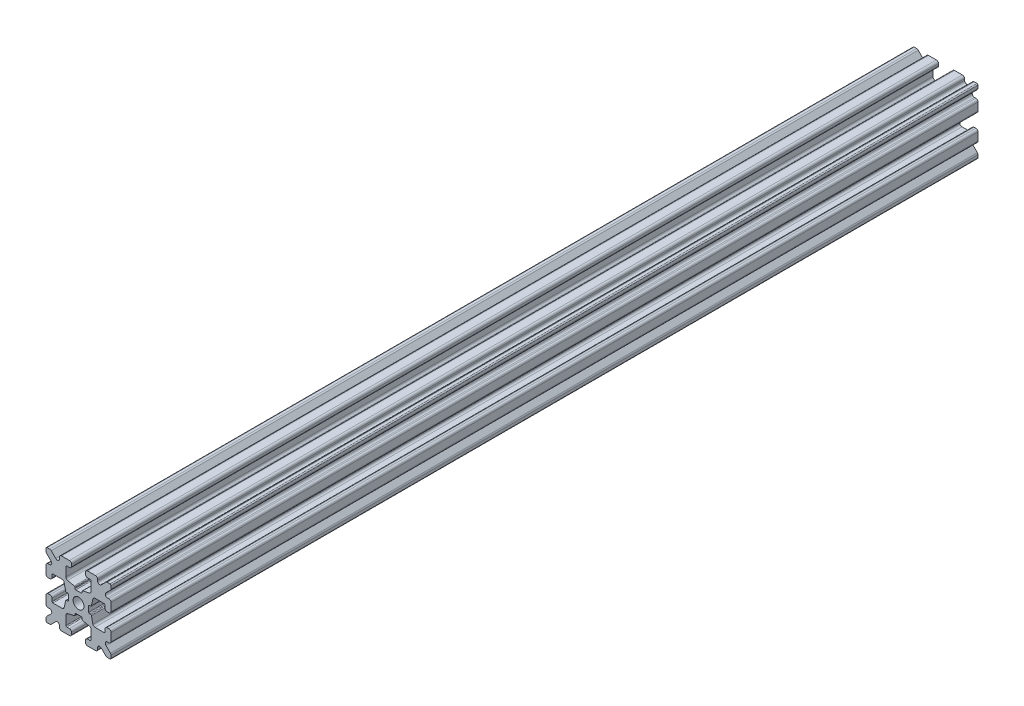
SolidWorks part; units mm, degrees
material "1060 Alloy"
ref_plane "Front Plane" through (0, 0, 0) normal (0, 0, 1) x (1, 0, 0)
ref_plane "Top Plane" through (0, 0, 0) normal (0, 1, 0) x (1, 0, 0)
ref_plane "Right Plane" through (0, 0, 0) normal (1, 0, 0) x (0, 0, -1)
sketch "Sketch1" plane through (0, 0, 0) normal (0, 0, 1) x (1, 0, 0)
  line L1 (-7.5, -7.5) -> (7.5, -7.5)
  line L2 (-7.5, -7.5) -> (-7.5, 7.5)
  line L3 (-7.5, 7.5) -> (7.5, 7.5)
  line L4 (7.5, -7.5) -> (7.5, 7.5)
  line L5 (-7.5, -7.5) -> (7.5, 7.5) construction
  line L6 (-7.5, 7.5) -> (7.5, -7.5) construction
  circle A0 centre (0, 0) radius 1.25
  point P0 (0, 0)
  dimension "D2" = 2.5
  dimension "D1" = 15
extrude "Boss-Extrude1" add sketch "Sketch1" along normal mid plane 200
fillet "Fillet1" radius 0.25 4 edges at (7.5, -7.5, 0) (-7.5, -7.5, 0) (7.5, 7.5, 0) (-7.5, 7.5, 0)
sketch "Sketch2" plane through (0, 0, 100) normal (0, 0, 1) x (1, 0, 0)
  line L0 (-7.5, 7.25) -> (-7.5, -7.25) construction
  line L1 (-7.5, 1.6) -> (-6.1, 1.6)
  line L2 (-7.5, 1.6) -> (-7.5, -1.6)
  line L3 (-7.5, -1.6) -> (-6.1, -1.6)
  line L4 (-6.1, 1.6) -> (-6.1, 2.9)
  line L5 (0, 0) -> (-12.1036, 0) construction
  line L6 (-6.1, -2.9) -> (-3.4, -2.9)
  line L7 (0, 0) -> (-7.25, 7.25) construction
  line L8 (-6.1, 2.9) -> (-3.4, 2.9)
  line L9 (-3.4, -2.9) -> (-3.4, 2.9)
  line L10 (55, 0) -> (-55, 0) construction
  line L11 (-6.1, -2.9) -> (-6.1, -1.6)
  line L12 (2.9, 6.1) -> (1.6, 6.1)
  line L13 (2.9, 3.4) -> (-2.9, 3.4)
  line L14 (-2.9, 6.1) -> (-2.9, 3.4)
  line L15 (2.9, 6.1) -> (2.9, 3.4)
  line L16 (-1.6, 6.1) -> (-2.9, 6.1)
  line L17 (1.6, 7.5) -> (1.6, 6.1)
  line L18 (-1.6, 7.5) -> (1.6, 7.5)
  line L19 (-1.6, 7.5) -> (-1.6, 6.1)
  line L20 (-1.6, -7.5) -> (-1.6, -6.1)
  line L21 (-1.6, -7.5) -> (1.6, -7.5)
  line L22 (1.6, -7.5) -> (1.6, -6.1)
  line L23 (-1.6, -6.1) -> (-2.9, -6.1)
  line L24 (2.9, -6.1) -> (2.9, -3.4)
  line L25 (-2.9, -6.1) -> (-2.9, -3.4)
  line L26 (2.9, -3.4) -> (-2.9, -3.4)
  line L27 (2.9, -6.1) -> (1.6, -6.1)
  line L28 (6.1, -2.9) -> (6.1, -1.6)
  line L29 (3.4, -2.9) -> (3.4, 2.9)
  line L30 (6.1, 2.9) -> (3.4, 2.9)
  line L31 (6.1, -2.9) -> (3.4, -2.9)
  line L32 (6.1, 1.6) -> (6.1, 2.9)
  line L33 (7.5, -1.6) -> (6.1, -1.6)
  line L34 (7.5, 1.6) -> (7.5, -1.6)
  line L35 (7.5, 1.6) -> (6.1, 1.6)
  dimension "D1" = 3.2
  dimension "D2" = 5.8
  dimension "D3" = 1.4
  dimension "D4" = 2.7
extrude "Cut-Extrude1" cut sketch "Sketch2" against normal through all
sketch "Sketch4" plane through (0, 0, 100) normal (0, 0, 1) x (1, 0, 0)
  line L0 (-3.4, 2.9) -> (-2.75, 0)
  line L1 (55, 0) -> (-55, 0) construction
  line L2 (-2.75, 0) -> (-3.4, -2.9)
  line L3 (-3.4, -2.9) -> (-3.4, 2.9) construction
  line L4 (-3.4, 2.9) -> (-3.4, -2.9)
  line L5 (-2.9, 3.4) -> (0, 2.75)
  line L6 (0, 2.75) -> (2.9, 3.4)
  line L7 (2.9, 3.4) -> (-2.9, 3.4)
  line L8 (3.4, 2.9) -> (2.75, 0)
  line L9 (2.75, 0) -> (3.4, -2.9)
  line L10 (3.4, -2.9) -> (3.4, 2.9)
  line L11 (-2.9, -3.4) -> (0, -2.75)
  line L12 (0, -2.75) -> (2.9, -3.4)
  line L13 (2.9, -3.4) -> (-2.9, -3.4)
  circle A2 centre (0, 0) radius 2.75
  circle A3 centre (0, 0) radius 2.75 construction
  dimension "D1" = 1.5
extrude "Cut-Extrude3" cut sketch "Sketch4" against normal through all
fillet "Fillet3" radius 0.5 16 edges at (-6.1, -1.6, 0) (-7.5, -1.6, 0) (-6.1, 1.6, 0) (-7.5, 1.6, 0) (-1.6, -7.5, 0) (-1.6, -6.1, 0) (1.6, -7.5, 0) (1.6, -6.1, 0) (6.1, -1.6, 0) (7.5, -1.6, 0) (7.5, 1.6, 0) (6.1, 1.6, 0) (1.6, 7.5, 0) (1.6, 6.1, 0) (-1.6, 7.5, 0) (-1.6, 6.1, 0)
fillet "Fillet4" radius 0.5 8 edges at (-3.4, 2.9, 0) (-3.4, -2.9, 0) (2.9, -3.4, 0) (-2.9, -3.4, 0) (3.4, -2.9, 0) (3.4, 2.9, 0) (-2.9, 3.4, 0) (2.9, 3.4, 0)
fillet "Fillet5" radius 3 4 edges at (0, -2.75, 0) (2.75, 0, 0) (-2.75, 0, 0) (0, 2.75, 0)
fillet "Fillet6" radius 0.2 8 edges at (-2.9, -6.1, 0) (2.9, -6.1, 0) (6.1, -2.9, 0) (6.1, 2.9, 0) (2.9, 6.1, 0) (-2.9, 6.1, 0) (-6.1, -2.9, 0) (-6.1, 2.9, 0)
sketch "Sketch5" plane through (0, 0, 100) normal (0, 0, 1) x (1, 0, 0)
  line L0 (0, 0) -> (-7.25, 7.25) construction
  line L1 (-7.5, 6.4393) -> (-5.4607, 4.4)
  line L2 (-6.4393, 7.5) -> (-4.4, 5.4607)
  line L3 (-7.5, 4.4) -> (-5.4607, 4.4)
  line L4 (-3.8003, 2.9) -> (-5.9, 2.9) construction
  line L5 (0, 0) -> (-12.1819, 0) construction
  line L6 (-4.4, 7.5) -> (-4.4, 5.4607)
  line L7 (-2.9, 5.9) -> (-2.9, 3.8003) construction
  line L8 (-7.5, 6.4393) -> (-7.5, 4.4)
  line L9 (-7.5, 7.25) -> (-7.5, 2.1) construction
  line L10 (2.1, -7.5) -> (7.25, -7.5) construction
  line L11 (7.5, -7.25) -> (7.5, -2.1) construction
  line L12 (7.25, 7.5) -> (2.1, 7.5) construction
  line L13 (-2.1, 7.5) -> (-7.25, 7.5) construction
  line L14 (-4.4, 7.5) -> (-6.4393, 7.5)
  line L16 (55, 0) -> (-55, 0) construction
  line L17 (0, 0) -> (0, 10.993) construction
  line L18 (0, -54.6431) -> (0, 54.6431) construction
  line L20 (4.4, 7.5) -> (6.4393, 7.5)
  line L22 (7.5, 6.4393) -> (7.5, 4.4)
  line L23 (4.4, 7.5) -> (4.4, 5.4607)
  line L24 (7.5, 4.4) -> (5.4607, 4.4)
  line L25 (6.4393, 7.5) -> (4.4, 5.4607)
  line L26 (7.5, 6.4393) -> (5.4607, 4.4)
  line L27 (7.5, -6.4393) -> (5.4607, -4.4)
  line L28 (6.4393, -7.5) -> (4.4, -5.4607)
  line L29 (7.5, -4.4) -> (5.4607, -4.4)
  line L30 (4.4, -7.5) -> (4.4, -5.4607)
  line L31 (7.5, -6.4393) -> (7.5, -4.4)
  line L33 (4.4, -7.5) -> (6.4393, -7.5)
  line L36 (-4.4, -7.5) -> (-6.4393, -7.5)
  line L38 (-7.5, -6.4393) -> (-7.5, -4.4)
  line L39 (-4.4, -7.5) -> (-4.4, -5.4607)
  line L40 (-7.5, -4.4) -> (-5.4607, -4.4)
  line L41 (-6.4393, -7.5) -> (-4.4, -5.4607)
  line L42 (-7.5, -6.4393) -> (-5.4607, -4.4)
  dimension "D1" = 1.5
  dimension "D2" = 1.5
  dimension "D3" = 1.5
extrude "Cut-Extrude4" cut sketch "Sketch5" against normal through all
fillet "Fillet8" radius 0.5 24 edges at (-5.4607, 4.4, 0) (-7.5, 4.4, 0) (-5.4607, -4.4, 0) (-7.5, -4.4, 0) (-4.4, -7.5, 0) (-4.4, -5.4607, 0) (4.4, -7.5, 0) (4.4, -5.4607, 0) (5.4607, -4.4, 0) (7.5, -4.4, 0) (7.5, 4.4, 0) (5.4607, 4.4, 0) (4.4, 5.4607, 0) (4.4, 7.5, 0) (-4.4, 5.4607, 0) (-4.4, 7.5, 0) (-6.4393, 7.5, 0) (-7.5, 6.4393, 0) (6.4393, 7.5, 0) (7.5, 6.4393, 0) (6.4393, -7.5, 0) (7.5, -6.4393, 0) (-6.4393, -7.5, 0) (-7.5, -6.4393, 0)
sketch "Sketch6" plane through (0, 0, 100) normal (0, 0, 1) x (1, 0, 0)
  line L0 (0, 0) -> (0, 11.013) construction
  line L1 (0.6561, 2.8971) -> (2.1235, 2.8971) construction
  line L2 (0, -54.6431) -> (0, 54.6431) construction
  line L3 (0, 0) -> (7.25, 7.25) construction
  line L4 (7.5, 0.8255) -> (7.5, -0.8255)
  line L5 (2.3471, 0.8255) -> (7.5, 0.8255)
  line L6 (0, 0) -> (12.4016, 0) construction
  line L7 (0.8255, -7.5) -> (-0.8255, -7.5)
  line L8 (2.3471, -0.8255) -> (2.3471, 0.8255)
  line L9 (0.8255, -2.3471) -> (0.8255, -7.5)
  line L10 (7.5, -0.8255) -> (2.3471, -0.8255)
  line L11 (-7.5, -0.8255) -> (-2.3471, -0.8255)
  line L12 (-2.3471, -0.8255) -> (-2.3471, 0.8255)
  line L13 (-0.8255, -2.3471) -> (0.8255, -2.3471)
  line L14 (-0.8255, 7.5) -> (-0.8255, 2.3471)
  line L15 (-0.8255, 2.3471) -> (0.8255, 2.3471)
  line L16 (-0.8255, -7.5) -> (-0.8255, -2.3471)
  line L17 (0.8255, 2.3471) -> (0.8255, 7.5)
  line L18 (0.8255, 7.5) -> (-0.8255, 7.5)
  line L19 (3.9, 7.5) -> (2.1, 7.5) construction
  line L20 (-2.3471, 0.8255) -> (-7.5, 0.8255)
  line L21 (-7.5, 0.8255) -> (-7.5, -0.8255)
  point P5 (0, -2.5973)
  point P7 (0, 2.5973)
  dimension "D3" = 0.55
  dimension "D1" = 1.651
extrude "Cut-Extrude5" cut sketch "Sketch6" against normal through all
fillet "Fillet10" radius 0.2 16 edges at (-2.935, 0.8255, 0) (-2.935, -0.8255, 0) (2.935, -0.8255, 0) (2.935, 0.8255, 0) (0.8255, 2.935, 0) (-0.8255, 2.935, 0) (-2.3471, 0.8255, 0) (-2.3471, -0.8255, 0) (0.8255, 2.3471, 0) (-0.8255, 2.3471, 0) (2.3471, 0.8255, 0) (2.3471, -0.8255, 0) (0.8255, -2.935, 0) (0.8255, -2.3471, 0) (-0.8255, -2.3471, 0) (-0.8255, -2.935, 0)
